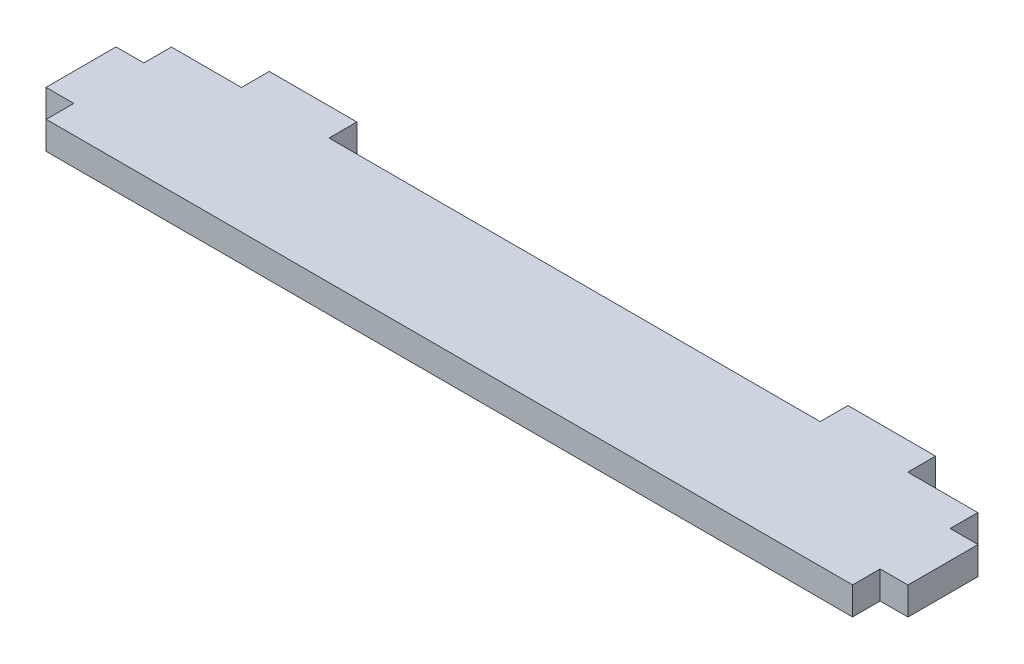
SolidWorks part; units mm, degrees
material "Acrylic (Medium-high impact)"
ref_plane "Front Plane" through (0, 0, 0) normal (0, 0, 1) x (1, 0, 0)
ref_plane "Top Plane" through (0, 0, 0) normal (0, 1, 0) x (1, 0, 0)
ref_plane "Right Plane" through (0, 0, 0) normal (1, 0, 0) x (0, 0, -1)
sketch "Sketch1" plane through (0, 0, 0) normal (0, 1, 0) x (1, 0, 0)
  line L1 (46.05, -7.15) -> (-46.05, -7.15)
  line L2 (46.05, -7.15) -> (46.05, 7.15)
  line L3 (46.05, 7.15) -> (-46.05, 7.15)
  line L4 (-46.05, -7.15) -> (-46.05, 7.15)
  line L5 (46.05, -7.15) -> (-46.05, 7.15) construction
  line L6 (46.05, 7.15) -> (-46.05, -7.15) construction
  point P0 (0, 0)
  dimension "D1" = 14.3
  dimension "D2" = 92.1
extrude "Boss-Extrude1" add sketch "Sketch1" along normal blind 3.175
sketch "Sketch2" plane through (0, 0, -7.15) normal (0, 0, -1) x (-1, 0, 0)
  line L0 (-46.05, 0) -> (46.05, 0) construction
  line L1 (-38.05, 0) -> (-28.05, 0)
  line L2 (-38.05, 0) -> (-38.05, 3.175)
  line L3 (-38.05, 3.175) -> (-28.05, 3.175)
  line L4 (-28.05, 0) -> (-28.05, 3.175)
  line L5 (-46.05, 3.175) -> (46.05, 3.175) construction
  line L6 (-46.05, 3.175) -> (-46.05, 0) construction
  line L7 (0, 1.7463) -> (0, -1.7463) construction
  line L8 (38.05, 3.175) -> (28.05, 3.175)
  line L9 (28.05, 0) -> (28.05, 3.175)
  line L10 (38.05, 0) -> (28.05, 0)
  line L11 (38.05, 0) -> (38.05, 3.175)
  dimension "D1" = 8
  dimension "D2" = 10
extrude "Boss-Extrude2" add sketch "Sketch2" along normal blind 3.175
sketch "Sketch3" plane through (-46.05, 0, 0) normal (-1, 0, 0) x (0, 0, 1)
  line L0 (-7.15, 0) -> (7.15, 0) construction
  line L1 (-4, 0) -> (4, 0)
  line L2 (-4, 0) -> (-4, 3.175)
  line L3 (-4, 3.175) -> (4, 3.175)
  line L4 (4, 0) -> (4, 3.175)
  line L5 (-7.15, 3.175) -> (7.15, 3.175) construction
  dimension "D1" = 8
extrude "Boss-Extrude3" add sketch "Sketch3" along normal blind 3.175
mirror "Mirror1" about plane through (0, 0, 0) normal (1, 0, 0) of "Boss-Extrude3"
